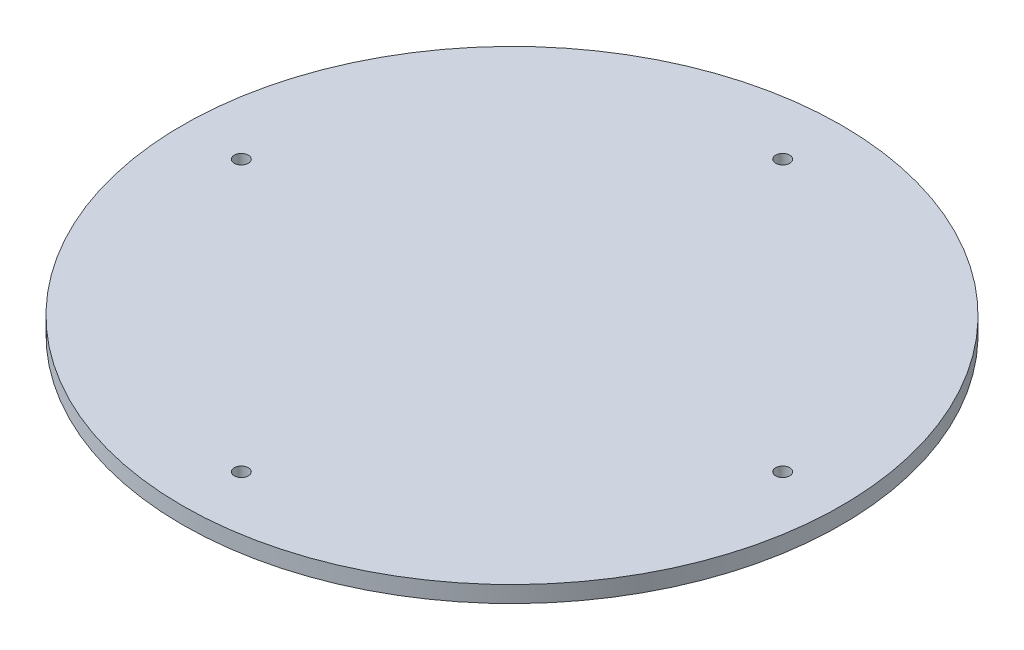
SolidWorks part; units mm, degrees
ref_plane "Front Plane" through (0, 0, 0) normal (0, 0, 1) x (1, 0, 0)
ref_plane "Top Plane" through (0, 0, 0) normal (0, 1, 0) x (1, 0, 0)
ref_plane "Right Plane" through (0, 0, 0) normal (1, 0, 0) x (0, 0, -1)
sketch "Sketch1" plane through (0, 0, 0) normal (0, 1, 0) x (1, 0, 0)
  circle A0 centre (0, 0) radius 70
  dimension "D1" = 140
extrude "Boss-Extrude1" add sketch "Sketch1" along normal blind 3.5
sketch "Sketch2" plane through (0, 3.5, 0) normal (0, 1, 0) x (1, 0, 0)
  line L0 (0, 0) -> (57.5, 0)
  circle A0 centre (57.5, 0) radius 1.5
  dimension "D2" = 3
  dimension "D1" = 57.5
extrude "Cut-Extrude1" cut sketch "Sketch2" against normal blind 3.5 contours A0
pattern_circular "CirPattern1" count 4 over 360 about axis through (0, 0, 0) along (0, 1, 0) of "Cut-Extrude1"
